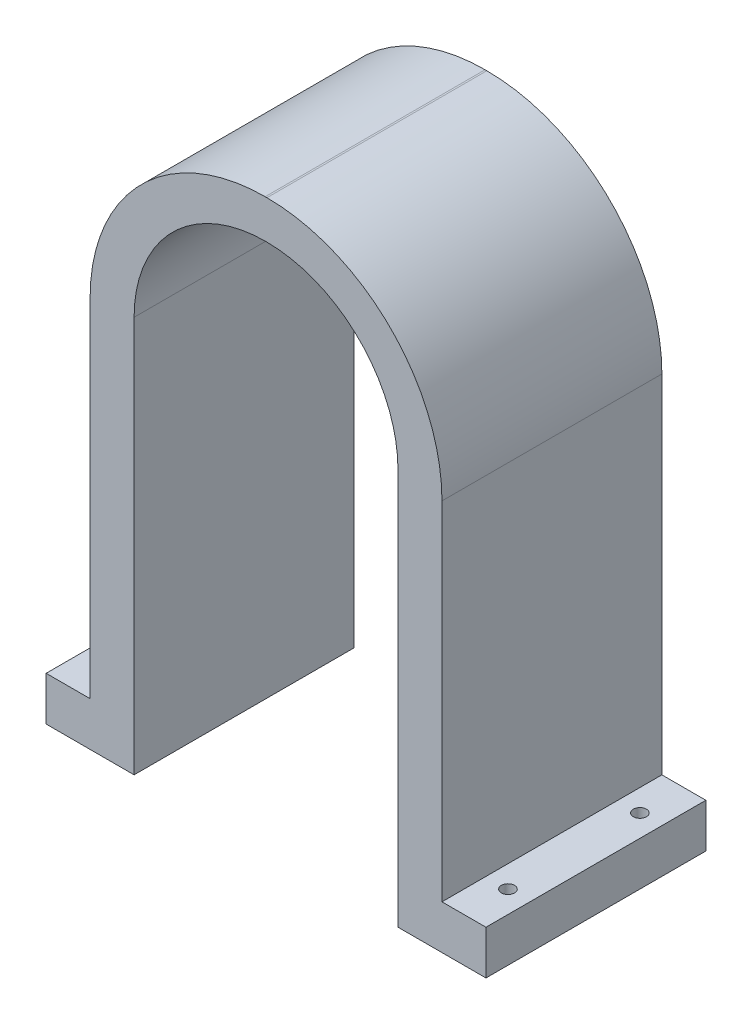
SolidWorks part; units mm, degrees
ref_plane "Front Plane" through (0, 0, 0) normal (0, 0, 1) x (1, 0, 0)
ref_plane "Top Plane" through (0, 0, 0) normal (0, 1, 0) x (1, 0, 0)
ref_plane "Right Plane" through (0, 0, 0) normal (1, 0, 0) x (0, 0, -1)
sketch "Sketch1" plane through (0, 0, 0) normal (0, 0, 1) x (1, 0, 0)
  line L0 (-7.4528, -1.2358) -> (-7.4528, -11.2358)
  line L1 (-7.4528, -1.2358) -> (2.5472, -1.2358)
  line L2 (-7.4528, -11.2358) -> (12.5472, -11.2358)
  line L3 (2.5472, -1.2358) -> (2.5472, 77.7041)
  line L4 (2.5472, -1.2358) -> (82.5472, -1.2358) construction
  line L5 (82.5472, -1.2358) -> (82.5472, 77.7041)
  line L6 (82.5472, -1.2358) -> (92.5472, -1.2358)
  line L7 (12.5472, -11.2358) -> (12.5472, 78.8642)
  line L8 (92.5472, -1.2358) -> (92.5472, -11.2358)
  line L9 (92.5472, -11.2358) -> (72.5472, -11.2358)
  line L10 (72.5472, -11.2358) -> (72.5472, 78.8642)
  line L11 (42.4472, 108.7642) -> (42.6472, 108.7642)
  line L12 (42.3472, 117.5041) -> (42.7472, 117.5041)
  arc A0 (42.4472, 108.7642) -> (12.5472, 78.8642) centre (42.4472, 78.8642) ccw
  arc A1 (72.5472, 78.8642) -> (42.6472, 108.7642) centre (42.6472, 78.8642) ccw
  arc A2 (42.3472, 117.5041) -> (2.5472, 77.7041) centre (42.3472, 77.7041) ccw
  arc A3 (82.5472, 77.7041) -> (42.7472, 117.5041) centre (42.7472, 77.7041) ccw
  point P14 (12.5472, 108.7642)
  point P17 (72.5472, 108.7642)
  point P20 (2.5472, 117.5041)
  point P21 (-99.5555, 55.2262)
  point P22 (-124.3785, 178.2259)
  dimension "D4" = 118.74
  dimension "D5" = 80
  dimension "D10" = 29.9
  dimension "D11" = 29.9
  dimension "D12" = 39.8
  dimension "D13" = 39.8
  dimension "D1" = 10
  dimension "D2" = 10
  dimension "D3" = 20
  dimension "D6" = 120
  dimension "10mm" = 10
  dimension "D7" = 10
  dimension "D8" = 20
  dimension "D9" = 120
extrude "Boss-Extrude2" add sketch "Sketch1" along normal blind 50
sketch "Sketch3" plane through (0, -1.2358, 0) normal (0, 1, 0) x (1, 0, 0)
  line L0 (-2.4528, -50) -> (-2.4528, -40) construction
  line L1 (2.5472, -50) -> (-7.4528, -50) construction
  line L2 (-2.4528, 0) -> (-2.4528, -10) construction
  line L3 (2.5472, 0) -> (-7.4528, 0) construction
  line L4 (87.5472, -50) -> (87.5472, -40) construction
  line L5 (92.5472, -50) -> (82.5472, -50) construction
  line L6 (87.5472, 0) -> (87.5472, -10) construction
  line L7 (92.5472, 0) -> (82.5472, 0) construction
  circle A0 centre (-2.4528, -40) radius 1.5
  circle A1 centre (-2.4528, -10) radius 1.5
  circle A2 centre (87.5472, -10) radius 1.5
  circle A3 centre (87.5472, -40) radius 1.5
  dimension "D2" = 3
  dimension "D4" = 3
  dimension "D7" = 3
  dimension "D8" = 3
  dimension "D1" = 10
  dimension "D3" = 10
  dimension "D5" = 10
  dimension "D6" = 10
extrude "Cut-Extrude1" cut sketch "Sketch3" against normal blind 50
